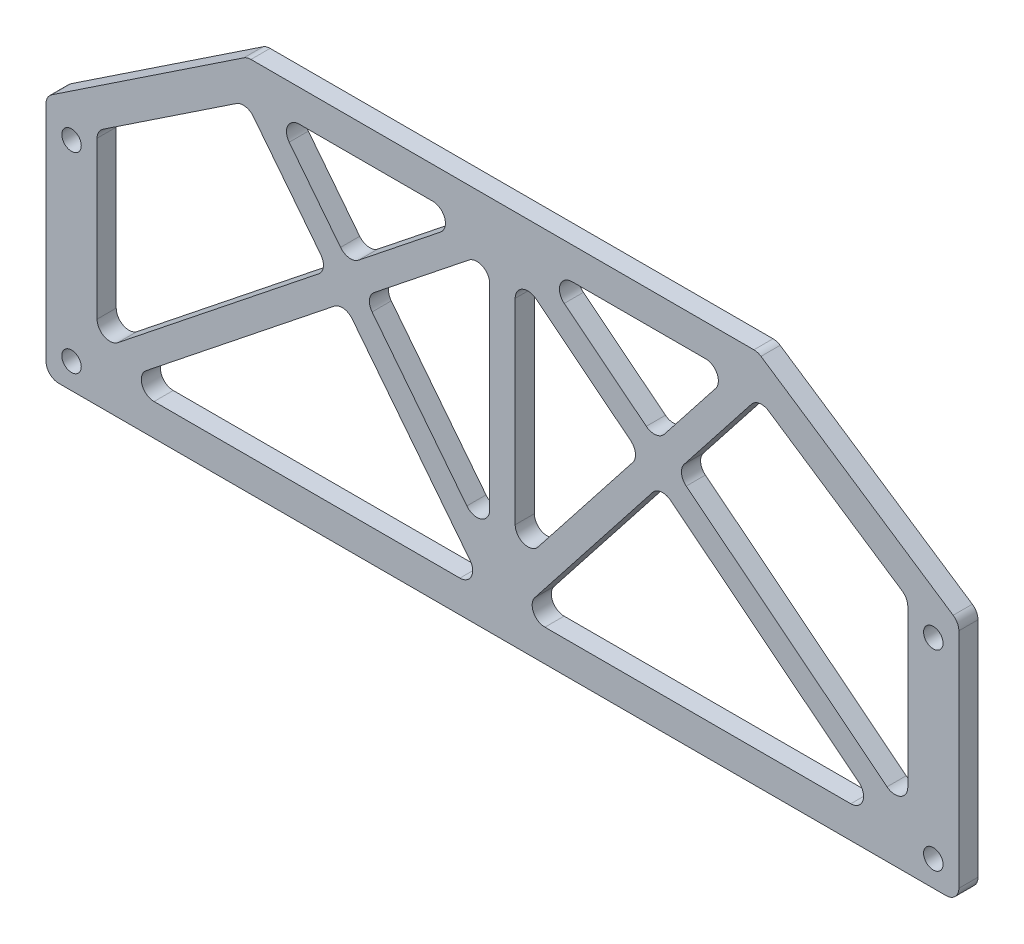
SolidWorks part; units mm, degrees
material "A-玻璃纤维"
ref_plane "前视基准面" through (0, 0, 0) normal (0, 0, 1) x (1, 0, 0)
ref_plane "上视基准面" through (0, 0, 0) normal (0, 1, 0) x (1, 0, 0)
ref_plane "右视基准面" through (0, 0, 0) normal (1, 0, 0) x (0, 0, -1)
other "Configuration Table"
sketch "草图1" plane through (0, 0, 0) normal (0, 0, 1) x (1, 0, 0)
  line L0 (-71.5, 19) -> (-40, 40)
  line L1 (-67.5, -15) -> (67.5, -15) construction
  line L2 (-67.5, -15) -> (-67.5, 15) construction
  line L3 (-67.5, 15) -> (67.5, 15) construction
  line L4 (67.5, -15) -> (67.5, 15) construction
  line L5 (-67.5, -15) -> (67.5, 15) construction
  line L6 (-67.5, 15) -> (67.5, -15) construction
  line L7 (-71.5, -19) -> (71.5, -19)
  line L8 (-71.5, -19) -> (-71.5, 19)
  line L10 (71.5, -19) -> (71.5, 19)
  line L11 (-71.5, -19) -> (71.5, 19) construction
  line L12 (-71.5, 19) -> (71.5, -19) construction
  line L13 (-40, 40) -> (40, 40)
  line L14 (40, 40) -> (71.5, 19)
  line L15 (0, 40) -> (0, 15) construction
  circle A0 centre (67.5, 15) radius 1.525
  circle A1 centre (67.5, -15) radius 1.525
  circle A2 centre (-67.5, -15) radius 1.525
  circle A3 centre (-67.5, 15) radius 1.525
  point P0 (0, 0)
  point P10 (0, 0)
  dimension "D3" = 3.05
  dimension "D1" = 30
  dimension "D2" = 135
  dimension "D4" = 4
  dimension "D5" = 4
  dimension "D6" = 4
  dimension "D7" = 25
  dimension "D8" = 80
extrude "凸台-拉伸1" add sketch "草图1" along normal mid plane 3
fillet "圆角1" radius 2 6 edges at (-71.5, -19, 0) (-71.5, 19, 0) (-40, 40, 0) (40, 40, 0) (71.5, 19, 0) (71.5, -19, 0)
sketch "草图2" plane through (0, 0, 1.5) normal (0, 0, 1) x (1, 0, 0)
  line L0 (-38.4861, 35) -> (-63.5, 18.3241)
  line L1 (-63.5, 18.3241) -> (-63.5, -14)
  line L2 (-63.5, -14) -> (63.5, -14)
  line L3 (63.5, -14) -> (63.5, 18.3241)
  line L4 (63.5, 18.3241) -> (38.4861, 35)
  line L5 (38.4861, 35) -> (-38.4861, 35)
  line L6 (39.3944, 40) -> (-39.3944, 40) construction
  line L7 (70.6094, 19.5937) -> (40.5038, 39.6641) construction
  line L8 (0, 0) -> (0, -14) construction
  line L9 (-69.5, -19) -> (69.5, -19) construction
  line L10 (-40.5038, 39.6641) -> (-70.6094, 19.5937) construction
  line L11 (-38.4861, 35) -> (0, -14) construction
  line L12 (0, -14) -> (38.4861, 35) construction
  line L13 (-40.059, 33.7646) -> (0, -17.2379)
  line L14 (0, -17.2379) -> (40.059, 33.7646)
  line L15 (-36.9133, 36.2354) -> (0, -10.7621)
  line L16 (0, -10.7621) -> (36.9133, 36.2354)
  line L17 (-40.059, 33.7646) -> (-36.9133, 36.2354)
  line L18 (40.059, 33.7646) -> (36.9133, 36.2354)
  line L19 (0, 35) -> (0, -10.7621) construction
  line L20 (-2, 35) -> (-2, -10.7621)
  line L21 (2, 35) -> (2, -10.7621)
  line L22 (-2, 35) -> (2, 35)
  line L23 (-2, -10.7621) -> (2, -10.7621)
  line L24 (-63.5, -14) -> (-2, 35) construction
  line L25 (2, 35) -> (63.5, -14) construction
  line L26 (0.7537, 33.4358) -> (62.2537, -15.5642)
  line L27 (-62.2537, -15.5642) -> (-0.7537, 33.4358)
  line L28 (3.2463, 36.5642) -> (64.7463, -12.4358)
  line L29 (-64.7463, -12.4358) -> (-3.2463, 36.5642)
  line L30 (0.7537, 33.4358) -> (3.2463, 36.5642)
  line L31 (62.2537, -15.5642) -> (64.7463, -12.4358)
  line L32 (-62.2537, -15.5642) -> (-64.7463, -12.4358)
  line L33 (-0.7537, 33.4358) -> (-3.2463, 36.5642)
  circle A0 centre (67.5, 15) radius 1.525 construction
  dimension "D1" = 4
  dimension "D2" = 5
  dimension "D3" = 5
  dimension "D4" = 5
  dimension "D5" = 5
  dimension "D6" = 2
  dimension "D7" = 2
  dimension "D8" = 2
  dimension "D9" = 2
  dimension "D10" = 2
  dimension "D11" = 2
extrude "切除-拉伸1" cut sketch "草图2" against normal mid plane 23 contours L27 L2 L13 | L1 L29 L13 L17 L0 | L15 L29 L5 | L27 L15 L20 | L26 L21 L16 | L5 L28 L16 | L14 L28 L3 L4 L18 | L26 L14 L2
sketch "草图3" plane through (0, 0, 1.5) normal (0, 0, 1) x (1, 0, 0)
  line L0 (40.059, 33.7646) -> (40.6767, 34.5511)
  line L1 (27.2417, 17.4459) -> (40.059, 33.7646) construction
  line L2 (40.6767, 34.5511) -> (38.4861, 35)
  line L3 (38.4861, 35) -> (40.059, 33.7646)
  dimension "D1" = 1
extrude "凸台-拉伸2" add sketch "草图3" against normal up to surface (3 mm away) up to face at (-8.5475, 13.6733, -1.5)
mirror "镜向1" about plane through (0, 0, 0) normal (1, 0, 0) of "凸台-拉伸2"
fillet "圆角2" radius 2 26 edges at (-2, 32.4428, 0) (-2, -8.2157, 0) (-21.6424, 16.7927, 0) (-5.2095, 35, 0) (-24.1132, 19.9385, 0) (-35.943, 35, 0) (63.5, 18.3241, 0) (63.5, -11.4428, 0) (27.2417, 17.4459, 0) (40.1553, 33.8872, 0) (-24.7709, 14.3001, 0) (-2.5431, -14, 0) (-60.2905, -14, 0) (24.1132, 19.9385, 0) (5.2095, 35, 0) (35.943, 35, 0) (24.7709, 14.3001, 0) (21.6424, 16.7927, 0) (2, -8.2157, 0) (2, 32.4428, 0) (-27.2417, 17.4459, 0) (-63.5, -11.4428, 0) (-63.5, 18.3241, 0) (-40.1553, 33.8872, 0) (60.2905, -14, 0) (2.5431, -14, 0)
equation "\"D6@草图1\"=\"D5@草图1\""
equation "\"D5@草图2\"=\"D4@草图2\""
